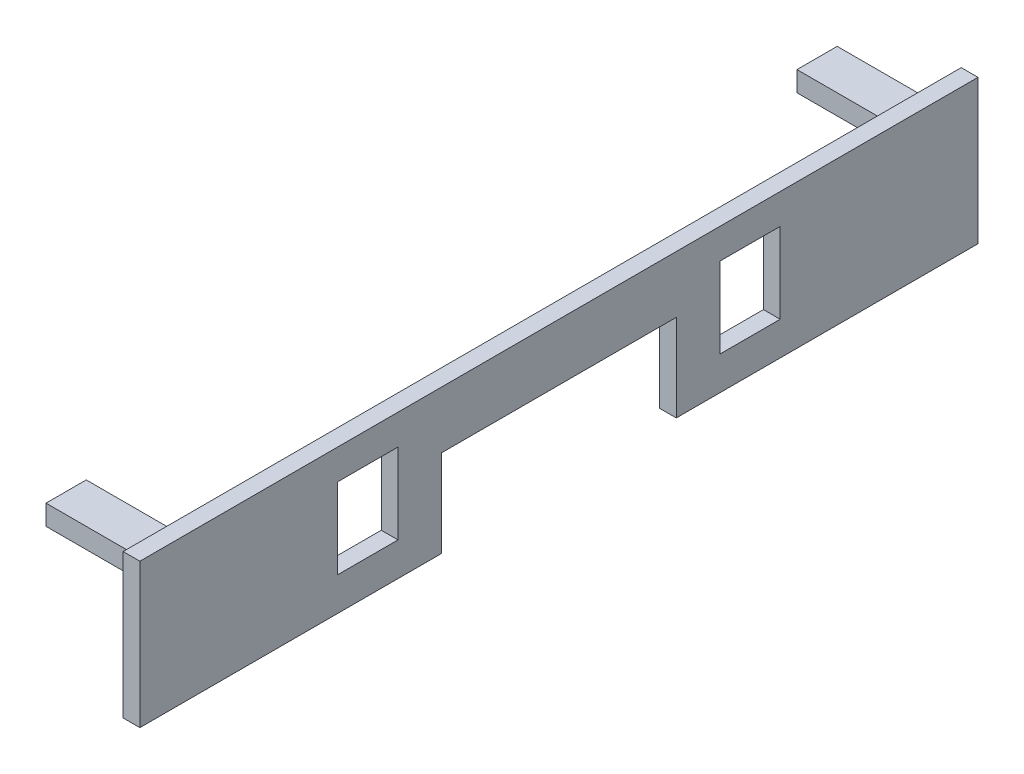
SolidWorks part; units mm, degrees
ref_plane "Front Plane" through (0, 0, 0) normal (0, 0, 1) x (1, 0, 0)
ref_plane "Top Plane" through (0, 0, 0) normal (0, 1, 0) x (1, 0, 0)
ref_plane "Right Plane" through (0, 0, 0) normal (1, 0, 0) x (0, 0, -1)
sketch "SK_P01_Bumperface" plane through (0, 0, 0) normal (0, 1, 0) x (1, 0, 0)
  line L0 (12.5, -48) -> (17.5, -48)
  line L1 (17.5, -48) -> (17.5, -35)
  line L2 (17.5, -35) -> (12.5, -35)
  line L3 (12.5, -35) -> (12.5, -48)
extrude "P01_Bumperface" add sketch "SK_P01_Bumperface" along normal blind 43
sketch "SK_P02_Bumperface" plane through (0, 0, 0) normal (0, 1, 0) x (1, 0, 0)
  line L0 (12.5, -125) -> (17.5, -125)
  line L1 (17.5, -125) -> (17.5, -66)
  line L2 (17.5, -66) -> (12.5, -66)
  line L3 (12.5, -66) -> (12.5, -125)
extrude "P02_Bumperface" add sketch "SK_P02_Bumperface" along normal blind 43
sketch "SK_P03_Bumperface" plane through (0, 0, 0) normal (0, 1, 0) x (1, 0, 0)
  line L0 (12.5, -66) -> (17.5, -66)
  line L1 (17.5, -66) -> (17.5, -48)
  line L2 (17.5, -48) -> (12.5, -48)
  line L3 (12.5, -48) -> (12.5, -66)
extrude "P03_Bumperface" add sketch "SK_P03_Bumperface" along normal blind 10
sketch "SK_P04_Bumperface" plane through (0, 0, 0) normal (0, 1, 0) x (1, 0, 0)
  line L0 (12.5, -66) -> (17.5, -66)
  line L1 (17.5, -66) -> (17.5, -48)
  line L2 (17.5, -48) -> (12.5, -48)
  line L3 (12.5, -48) -> (12.5, -66)
extrude "P04_Bumperface" add sketch "SK_P04_Bumperface" along normal blind 9 from offset 34
sketch "SK_P05_Flexurebracket" plane through (0, 0, 0) normal (0, 1, 0) x (1, 0, 0)
  line L0 (-17.5, -118) -> (12.5, -118)
  line L1 (12.5, -118) -> (12.5, -106)
  line L2 (12.5, -106) -> (-17.5, -106)
  line L3 (-17.5, -106) -> (-17.5, -118)
extrude "P05_Flexurebracket" add sketch "SK_P05_Flexurebracket" along normal blind 6 from offset 31
sketch "SK_P06_SwitchSS5GL2" plane through (0, 0, 0) normal (0, 1, 0) x (1, 0, 0)
  line L0 (6, -108) -> (12.5, -108)
  line L1 (12.5, -108) -> (12.5, -88)
  line L2 (12.5, -88) -> (6, -88)
  line L3 (6, -88) -> (6, -108)
extrude "P06_SwitchSS5GL2" add sketch "SK_P06_SwitchSS5GL2" along normal blind 10.2 from offset 20
sketch "SK_P07_Bumperface" plane through (0, 0, 0) normal (0, 1, 0) x (1, 0, 0)
  line L0 (12.5, 35) -> (17.5, 35)
  line L1 (17.5, 35) -> (17.5, 48)
  line L2 (17.5, 48) -> (12.5, 48)
  line L3 (12.5, 48) -> (12.5, 35)
extrude "P07_Bumperface" add sketch "SK_P07_Bumperface" along normal blind 43
sketch "SK_P08_Bumperface" plane through (0, 0, 0) normal (0, 1, 0) x (1, 0, 0)
  line L0 (12.5, 66) -> (17.5, 66)
  line L1 (17.5, 66) -> (17.5, 125)
  line L2 (17.5, 125) -> (12.5, 125)
  line L3 (12.5, 125) -> (12.5, 66)
extrude "P08_Bumperface" add sketch "SK_P08_Bumperface" along normal blind 43
sketch "SK_P09_Bumperface" plane through (0, 0, 0) normal (0, 1, 0) x (1, 0, 0)
  line L0 (12.5, 48) -> (17.5, 48)
  line L1 (17.5, 48) -> (17.5, 66)
  line L2 (17.5, 66) -> (12.5, 66)
  line L3 (12.5, 66) -> (12.5, 48)
extrude "P09_Bumperface" add sketch "SK_P09_Bumperface" along normal blind 10
sketch "SK_P10_Bumperface" plane through (0, 0, 0) normal (0, 1, 0) x (1, 0, 0)
  line L0 (12.5, 48) -> (17.5, 48)
  line L1 (17.5, 48) -> (17.5, 66)
  line L2 (17.5, 66) -> (12.5, 66)
  line L3 (12.5, 66) -> (12.5, 48)
extrude "P10_Bumperface" add sketch "SK_P10_Bumperface" along normal blind 9 from offset 34
sketch "SK_P11_Flexurebracket" plane through (0, 0, 0) normal (0, 1, 0) x (1, 0, 0)
  line L0 (-17.5, 106) -> (12.5, 106)
  line L1 (12.5, 106) -> (12.5, 118)
  line L2 (12.5, 118) -> (-17.5, 118)
  line L3 (-17.5, 118) -> (-17.5, 106)
extrude "P11_Flexurebracket" add sketch "SK_P11_Flexurebracket" along normal blind 6 from offset 31
sketch "SK_P12_SwitchSS5GL2" plane through (0, 0, 0) normal (0, 1, 0) x (1, 0, 0)
  line L0 (6, 88) -> (12.5, 88)
  line L1 (12.5, 88) -> (12.5, 108)
  line L2 (12.5, 108) -> (6, 108)
  line L3 (6, 108) -> (6, 88)
extrude "P12_SwitchSS5GL2" add sketch "SK_P12_SwitchSS5GL2" along normal blind 10.2 from offset 20
sketch "SK_P13_Bumperface" plane through (0, 0, 0) normal (0, 1, 0) x (1, 0, 0)
  line L0 (12.5, -35) -> (17.5, -35)
  line L1 (17.5, -35) -> (17.5, 35)
  line L2 (17.5, 35) -> (12.5, 35)
  line L3 (12.5, 35) -> (12.5, -35)
extrude "P13_Bumperface" add sketch "SK_P13_Bumperface" along normal blind 17 from offset 26
